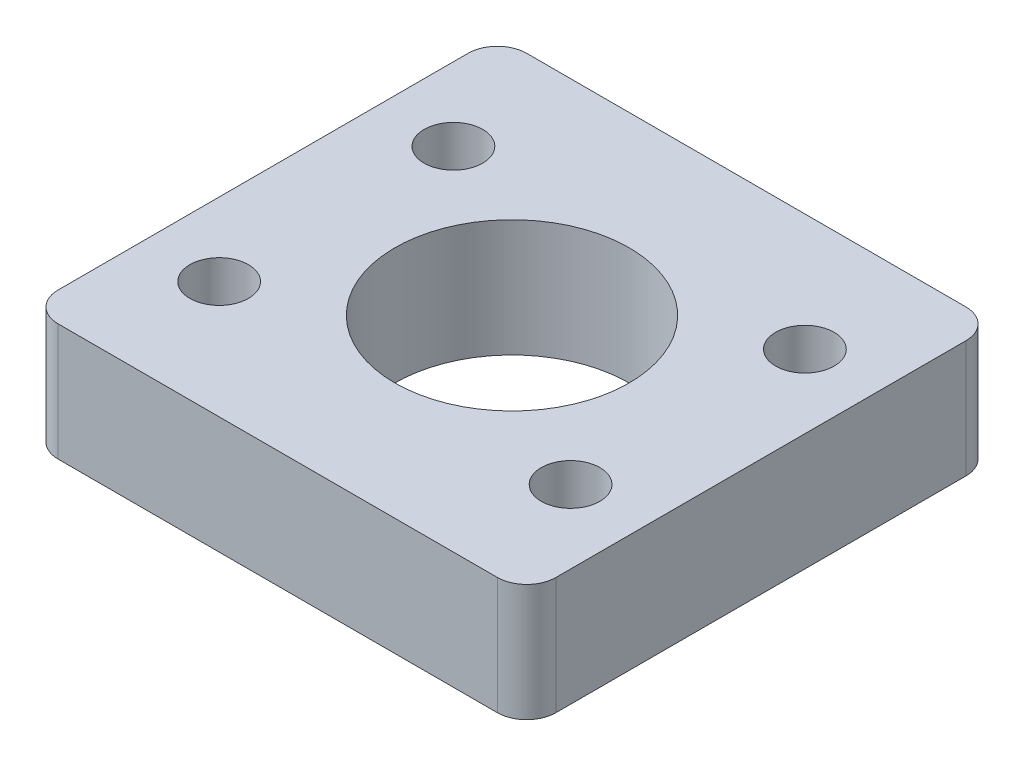
SolidWorks part; units mm, degrees
material "聚脂树脂"
ref_plane "前视基准面" through (0, 0, 0) normal (0, 0, 1) x (1, 0, 0)
ref_plane "上视基准面" through (0, 0, 0) normal (0, 1, 0) x (1, 0, 0)
ref_plane "右视基准面" through (0, 0, 0) normal (1, 0, 0) x (0, 0, -1)
other "Configuration Table"
sketch "草图1" plane through (0, 0, 0) normal (0, 1, 0) x (1, 0, 0)
  line L0 (0, 0) -> (0, 15.4433) construction
  line L1 (-8.5, -8) -> (8.5, -8)
  line L2 (-8.5, -8) -> (-8.5, 8)
  line L3 (-8.5, 8) -> (8.5, 8)
  line L4 (8.5, -8) -> (8.5, 8)
  line L5 (-8.5, -8) -> (8.5, 8) construction
  line L6 (-8.5, 8) -> (8.5, -8) construction
  line L7 (0, 0) -> (21.5354, 0) construction
  circle A0 centre (6, 4) radius 1
  circle A1 centre (-6, 4) radius 1
  circle A2 centre (6, -4) radius 1
  circle A3 centre (-6, -4) radius 1
  circle A4 centre (0, 0) radius 4
  point P0 (0, 0)
  dimension "D3" = 2
  dimension "D4" = 12
  dimension "D5" = 8
  dimension "D6" = 8
  dimension "D1" = 17
  dimension "D2" = 16
extrude "凸台-拉伸1" add sketch "草图1" along normal blind 4
fillet "圆角1" radius 1 4 edges at (8.5, 2, -8) (-8.5, 2, -8) (8.5, 2, 8) (-8.5, 2, 8)
